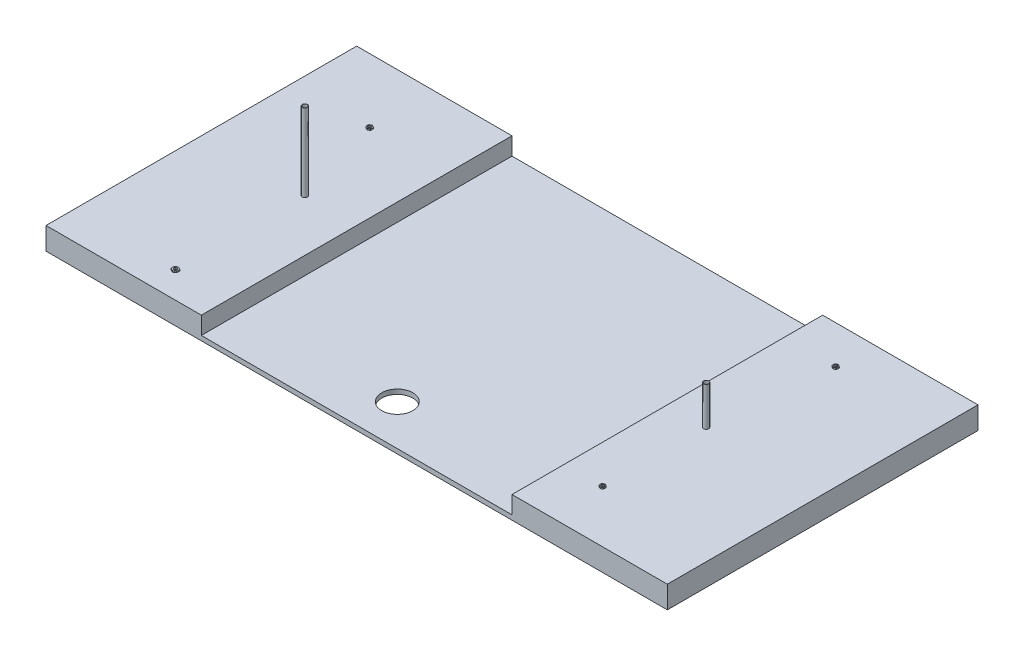
SolidWorks part; units mm, degrees
ref_plane "Front Plane" through (0, 0, 0) normal (0, 0, 1) x (1, 0, 0)
ref_plane "Top Plane" through (0, 0, 0) normal (0, 1, 0) x (1, 0, 0)
ref_plane "Right Plane" through (0, 0, 0) normal (1, 0, 0) x (0, 0, -1)
sketch "Sketch1" plane through (0, 0, 0) normal (0, 1, 0) x (1, 0, 0)
  line L0 (0, -55) -> (0, 55) construction
  line L5 (-1200, -600) -> (1200, -600)
  line L6 (-1200, -600) -> (-1200, 600)
  line L15 (-1200, 600) -> (1200, 600)
  line L16 (1200, -600) -> (1200, 600)
  line L17 (-1200, -600) -> (1200, 600) construction
  line L18 (-1200, 600) -> (1200, -600) construction
  circle A4 centre (0, -443.0536) radius 60
  point P0 (0, 0)
  point P5 (0, 0)
  dimension "D3" = 120
  dimension "D1" = 2400
  dimension "D2" = 1200
  dimension "D4" = 156.9464
  dimension "D5" = 1200
extrude "Boss-Extrude1" add sketch "Sketch1" along normal blind 18
sketch "Sketch2" plane through (0, 0, 0) normal (0, 1, 0) x (1, 0, 0)
  line L0 (-1200, -600) -> (1200, -600) construction
  line L1 (-1200, 600) -> (-600, 600)
  line L2 (-1200, 600) -> (-1200, -600)
  line L3 (-1200, -600) -> (-600, -600)
  line L4 (-600, 600) -> (-600, -600)
  line L6 (1200, 600) -> (600, 600)
  line L7 (1200, 600) -> (1200, -600)
  line L8 (1200, -600) -> (600, -600)
  line L9 (600, 600) -> (600, -600)
  dimension "D1" = 600
  dimension "D2" = 600
extrude "Boss-Extrude2" add sketch "Sketch2" along normal blind 68 from surface at 18 starting at face at (0, 18, 0)
sketch "Sketch3" plane through (0, 86, 0) normal (0, 1, 0) x (1, 0, 0)
  line L0 (-47.3, 0) -> (47.3, 0) construction
  line L1 (-600, -600) -> (-600, 600) construction
  circle A0 centre (-800, 0) radius 10
  circle A1 centre (-800, 0) radius 9
  dimension "D2" = 20
  dimension "D3" = 18
  dimension "D1" = 200
extrude "Boss-Extrude3" add sketch "Sketch3" along normal blind 300
sketch "Sketch4" plane through (0, 86, 0) normal (0, 1, 0) x (1, 0, 0)
  line L0 (-212.3, 0) -> (212.3, 0) construction
  line L1 (600, 600) -> (600, -600) construction
  circle A0 centre (750, 0) radius 10
  circle A1 centre (750, 0) radius 9
  dimension "D2" = 20
  dimension "D3" = 18
  dimension "D1" = 150
extrude "Boss-Extrude4" add sketch "Sketch4" along normal blind 150
sketch "Sketch6" plane through (0, 86, 0) normal (0, 1, 0) x (1, 0, 0)
  line L0 (-1200, -600) -> (-600, -600) construction
  line L7 (-600, -600) -> (-600, 600) construction
  line L8 (-1200, 600) -> (-1200, -600) construction
  line L9 (-800, -512.2273) -> (-789.4108, -506.1137)
  line L10 (-789.4108, -506.1137) -> (-789.4108, -493.8863)
  line L11 (-789.4108, -493.8863) -> (-800, -487.7727)
  line L12 (-800, -487.7727) -> (-810.5892, -493.8863)
  line L13 (-810.5892, -493.8863) -> (-810.5892, -506.1137)
  line L14 (-810.5892, -506.1137) -> (-800, -512.2273)
  line L15 (-600, 600) -> (-1200, 600) construction
  line L17 (-900, 360.6178) -> (-909.1953, 355.3089)
  line L18 (-909.1953, 355.3089) -> (-909.1953, 344.6911)
  line L19 (-909.1953, 344.6911) -> (-900, 339.3822)
  line L20 (-900, 339.3822) -> (-890.8047, 344.6911)
  line L21 (-890.8047, 344.6911) -> (-890.8047, 355.3089)
  line L22 (-890.8047, 355.3089) -> (-900, 360.6178)
  circle A0 centre (-800, -500) radius 10.5892 construction
  circle A1 centre (-800, -500) radius 6
  circle A2 centre (-900, 350) radius 6
  circle A3 centre (-900, 350) radius 9.1953 construction
  dimension "D3" = 12
  dimension "D4" = 12
  dimension "D1" = 100
  dimension "D2" = 200
  dimension "D5" = 300
  dimension "D6" = 250
extrude "Boss-Extrude5" add sketch "Sketch6" along normal blind 5
sketch "Sketch7" plane through (0, 86, 0) normal (0, 1, 0) x (1, 0, 0)
  line L0 (600, -600) -> (1200, -600) construction
  line L1 (600, 600) -> (600, -600) construction
  line L3 (750, -410.255) -> (758.8811, -405.1275)
  line L4 (758.8811, -405.1275) -> (758.8811, -394.8725)
  line L5 (758.8811, -394.8725) -> (750, -389.745)
  line L6 (750, -389.745) -> (741.1189, -394.8725)
  line L7 (741.1189, -394.8725) -> (741.1189, -405.1275)
  line L8 (741.1189, -405.1275) -> (750, -410.255)
  line L9 (600, 600) -> (600, -600) construction
  line L11 (1200, 600) -> (600, 600) construction
  line L13 (800, 460.5083) -> (790.8995, 455.2542)
  line L14 (790.8995, 455.2542) -> (790.8995, 444.7458)
  line L15 (790.8995, 444.7458) -> (800, 439.4917)
  line L16 (800, 439.4917) -> (809.1005, 444.7458)
  line L17 (809.1005, 444.7458) -> (809.1005, 455.2542)
  line L18 (809.1005, 455.2542) -> (800, 460.5083)
  circle A0 centre (750, -400) radius 6
  circle A1 centre (800, 450) radius 6
  circle A2 centre (750, -400) radius 8.8811 construction
  circle A3 centre (800, 450) radius 9.1005 construction
  dimension "D1" = 12
  dimension "D2" = 12
  dimension "D3" = 200
  dimension "D4" = 150
  dimension "D5" = 200
  dimension "D6" = 150
extrude "Boss-Extrude6" add sketch "Sketch7" along normal blind 5
sketch "Sketch9" plane through (0, 91, 0) normal (0, 1, 0) x (1, 0, 0)
  line L0 (-800, -466.5) -> (-800, -533.5) construction
  line L1 (-800, -533.5) -> (-800, -466.5)
  arc A0 (-800, -533.5) -> (-800, -466.5) centre (-800, -500) ccw
  dimension "D1" = 33.5
